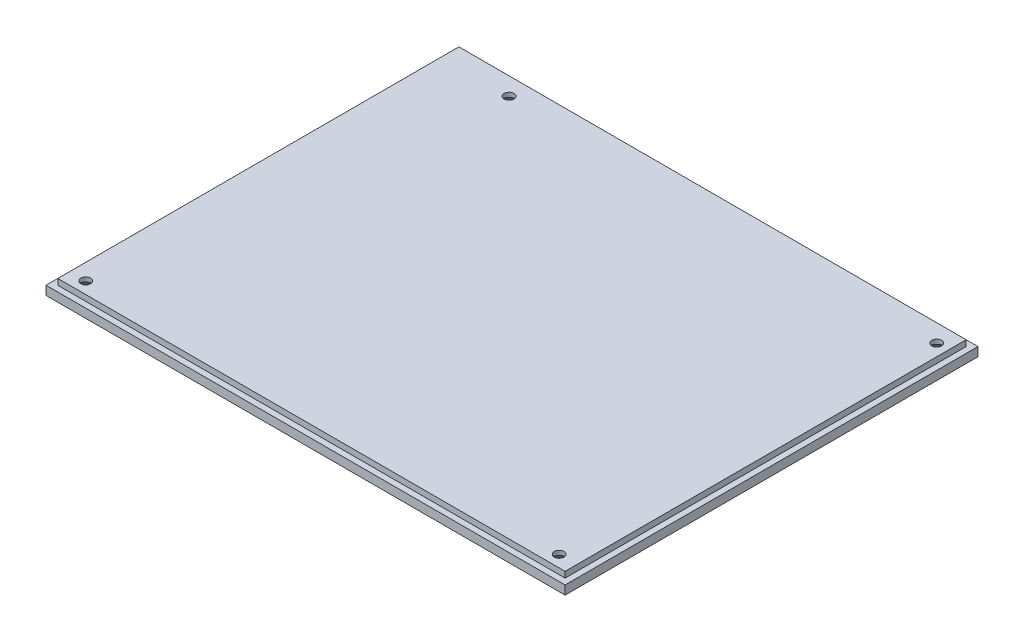
SolidWorks part; units mm, degrees
ref_plane "Front Plane" through (0, 0, 0) normal (0, 0, 1) x (1, 0, 0)
ref_plane "Top Plane" through (0, 0, 0) normal (0, 1, 0) x (1, 0, 0)
ref_plane "Right Plane" through (0, 0, 0) normal (1, 0, 0) x (0, 0, -1)
sketch "Sketch1" plane through (0, 0, 0) normal (0, 1, 0) x (1, 0, 0)
  line L1 (44, -35) -> (-44, -35)
  line L2 (44, -35) -> (44, 35)
  line L3 (44, 35) -> (-44, 35)
  line L4 (-44, -35) -> (-44, 35)
  line L5 (44, -35) -> (-44, 35) construction
  line L6 (44, 35) -> (-44, -35) construction
  point P0 (0, 0)
  dimension "D1" = 88
  dimension "D2" = 70
extrude "Boss-Extrude2" add sketch "Sketch1" along normal blind 1.5 contours L4 L3 L2 L1
sketch "Sketch7" plane through (0, 1.5, 0) normal (0, 1, 0) x (1, 0, 0)
  line L1 (43, -34) -> (-43, -34)
  line L2 (43, -34) -> (43, 34)
  line L3 (43, 34) -> (-43, 34)
  line L4 (-43, -34) -> (-43, 34)
  line L5 (43, -34) -> (-43, 34) construction
  line L6 (43, 34) -> (-43, -34) construction
  point P0 (0, 0)
  dimension "D1" = 68
  dimension "D2" = 86
extrude "Boss-Extrude3" add sketch "Sketch7" along normal blind 1
sketch "Sketch9" plane through (0, 2.5, 0) normal (0, 1, 0) x (1, 0, 0)
  line L1 (42, -33) -> (-42, -33)
  line L2 (42, -33) -> (42, 33)
  line L3 (42, 33) -> (-42, 33)
  line L4 (-42, -33) -> (-42, 33)
  line L5 (42, -33) -> (-42, 33) construction
  line L6 (42, 33) -> (-42, -33) construction
  point P0 (0, 0)
  dimension "D1" = 66
  dimension "D2" = 84
sketch "Sketch10" plane through (0, 0, 0) normal (0, -1, 0) x (1, 0, 0)
  line L0 (-44, 35) -> (-44, -35) construction
  line L1 (44, -35) -> (-44, -35) construction
  line L2 (44, 35) -> (44, -35) construction
  line L3 (44, 35) -> (-44, 35) construction
  circle A0 centre (-31.5, -31) radius 0.75
  circle A1 centre (-40.268, 32) radius 0.75
  circle A2 centre (40, 32) radius 0.75
  circle A3 centre (41, -31) radius 0.75
  point P8 (0, 0)
  point P17 (39.3255, 34.7126)
  point P20 (-40.3157, 35)
  dimension "D1" = 1.5
  dimension "D2" = 12.5
  dimension "D3" = 4
  dimension "D4" = 3
  dimension "D5" = 4
  dimension "D6" = 4
  dimension "D7" = 3
  dimension "D8" = 3.732
  dimension "D9" = 3
hole_wizard "CSK for M2.5 Flat Head Machine Screw1" positions "Sketch11" profile "Sketch12" countersink size "M2.5" standard "ANSI Metric"
sketch "Sketch11" plane through (0, 0, 0) normal (0, -1, 0) x (-1, 0, 0)
  point P0 (-40, -32)
  point P3 (-41, 31)
  point P6 (31.5, 31)
  point P9 (40.268, -32)
sketch "Sketch12" plane through (40, 0, 32) normal (1, 0, 0) x (0, 0, -1)
  line L0 (0, 0) -> (0, 3)
  line L1 (0, 3) -> (1.45, 2.1288)
  line L2 (1.45, 2.1288) -> (1.45, 1.3)
  line L3 (1.45, 1.3) -> (2.75, 0)
  line L5 (2.75, 0) -> (0, 0)
  line L6 (-1.45, 1.3) -> (-2.75, 0) construction
  line L10 (0, 3) -> (-1.45, 2.1288) construction
  line L11 (0, -6.35) -> (0, 107.95) construction
  dimension "Hole Dia." = 2.9
  dimension "Hole Depth" = 3
  dimension "Near C'Sink Dia." = 5.5
  dimension "Near C'Sink Angle" = 90
  dimension "Drill Angle" = 118
equation "\"3.5.00mm\"=2"
